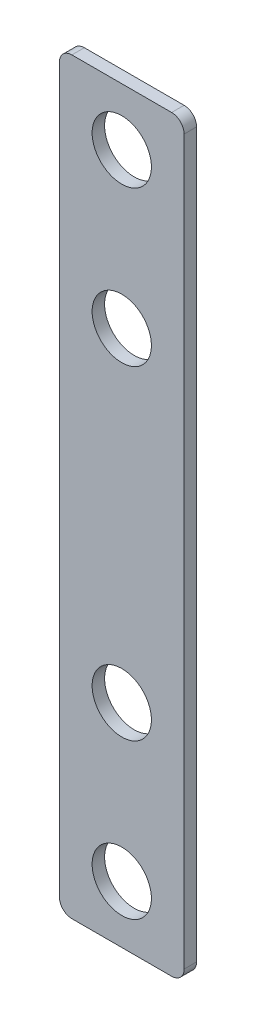
SolidWorks part; units mm, degrees
ref_plane "Front Plane" through (0, 0, 0) normal (0, 0, 1) x (1, 0, 0)
ref_plane "Top Plane" through (0, 0, 0) normal (0, 1, 0) x (1, 0, 0)
ref_plane "Right Plane" through (0, 0, 0) normal (1, 0, 0) x (0, 0, -1)
sketch "Sketch1" plane through (0, 0, 0) normal (0, 0, 1) x (1, 0, 0)
  line L1 (-25, 150) -> (25, 150)
  line L2 (-25, 150) -> (-25, -150)
  line L3 (-25, -150) -> (25, -150)
  line L4 (25, 150) -> (25, -150)
  dimension "D1" = 150
  dimension "D2" = 300
  dimension "D3" = 50
  dimension "D4" = 25
extrude "Boss-Extrude1" add sketch "Sketch1" along normal blind 5
fillet "Fillet3" radius 5 4 edges at (25, 150, 2.5) (25, -150, 2.5) (-25, -150, 2.5) (-25, 150, 2.5)
sketch "Sketch2" plane through (0, 0, 5) normal (0, 0, 1) x (1, 0, 0)
  line L0 (20, 150) -> (-20, 150) construction
  line L1 (-20, -150) -> (20, -150) construction
  circle A0 centre (0, 127) radius 12
  circle A1 centre (0, 65) radius 12
  circle A2 centre (0, -65) radius 12
  circle A3 centre (0, -127) radius 12
  point P8 (0, -127.5639)
  point P9 (0, -85.539)
  dimension "D1" = 62
  dimension "D2" = 23
  dimension "D3" = 23
  dimension "D4" = 62
hole_wizard "CBORE for M12 Hex Head Bolt1" positions "Sketch3" profile "Sketch4" counterbore size "M12" standard "BSI" end condition through all
sketch "Sketch3" plane through (0, 0, 5) normal (0, 0, 1) x (1, 0, 0)
  point P0 (0, 127)
  point P3 (0, 65)
  point P6 (0, -65)
  point P9 (0, -127)
sketch "Sketch4" plane through (0, 127, 5) normal (1, 0, 0) x (0, -1, 0)
  line L0 (0, 0) -> (0, 5)
  line L1 (0, 5) -> (6.75, 5)
  line L3 (6.75, 5) -> (6.75, 7.5)
  line L4 (6.75, 7.5) -> (11.8925, 7.5)
  line L5 (11.8925, 7.5) -> (11.8925, 0)
  line L7 (11.8925, 0) -> (0, 0)
  line L11 (0, -6.35) -> (0, 107.95) construction
  dimension "Thru Hole Dia." = 13.5
  dimension "Thru Hole Depth" = 5
  dimension "C'Bore Dia." = 23.785
  dimension "C'Bore Depth" = 7.5
